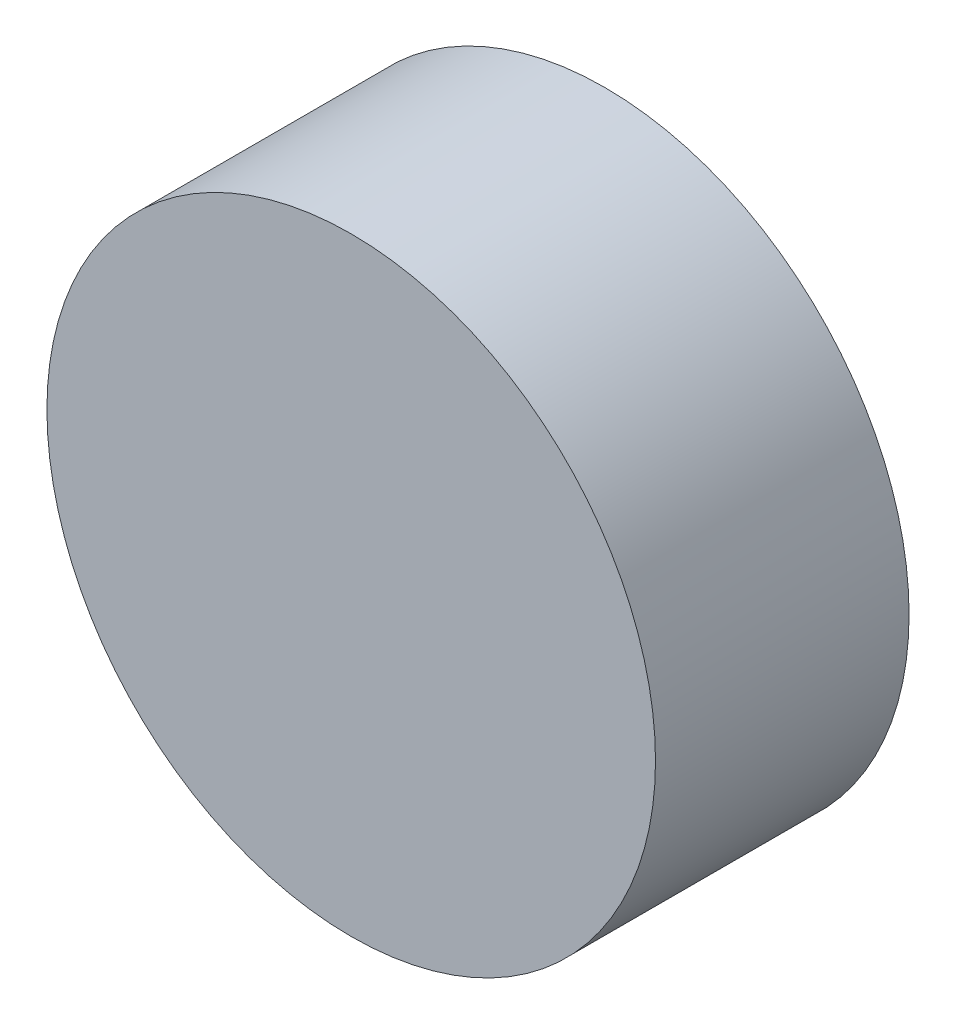
SolidWorks part; units mm, degrees
ref_plane "Front Plane" through (0, 0, 0) normal (0, 0, 1) x (1, 0, 0)
ref_plane "Top Plane" through (0, 0, 0) normal (0, 1, 0) x (1, 0, 0)
ref_plane "Right Plane" through (0, 0, 0) normal (1, 0, 0) x (0, 0, -1)
sketch "Sketch1" plane through (0, 0, 0) normal (0, 0, 1) x (1, 0, 0)
  circle A0 centre (0, 0) radius 3
  dimension "D1" = 6
extrude "Boss-Extrude1" add sketch "Sketch1" along normal blind 2.5
